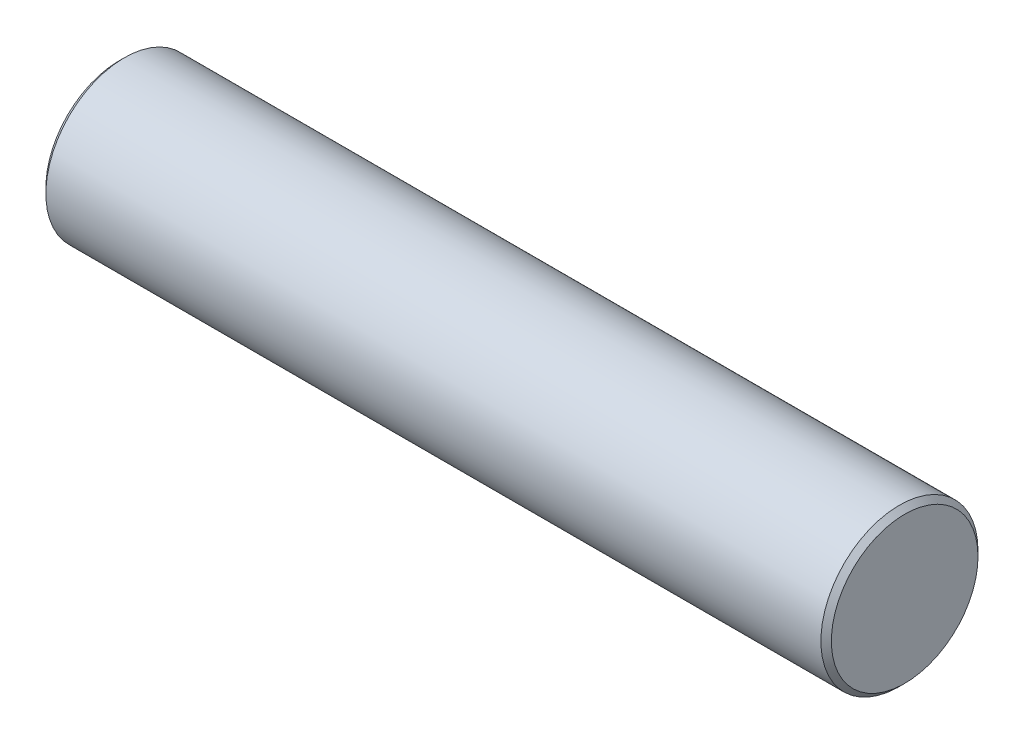
SolidWorks part; units mm, degrees
material "AISI 1045 Steel, cold drawn"
ref_plane "Front Plane" through (0, 0, 0) normal (0, 0, 1) x (1, 0, 0)
ref_plane "Top Plane" through (0, 0, 0) normal (0, 1, 0) x (1, 0, 0)
ref_plane "Right Plane" through (0, 0, 0) normal (1, 0, 0) x (0, 0, -1)
sketch "Sketch1" plane through (0, 0, 0) normal (1, 0, 0) x (0, 0, -1)
  circle A0 centre (0, 0) radius 1.5
  dimension "D1" = 3
extrude "Boss-Extrude1" add sketch "Sketch1" along normal mid plane 15
chamfer "Chamfer1" distance 0.1 angle 45 2 edges at (-7.5, 0, -1.5) (7.5, 0, -1.5)
